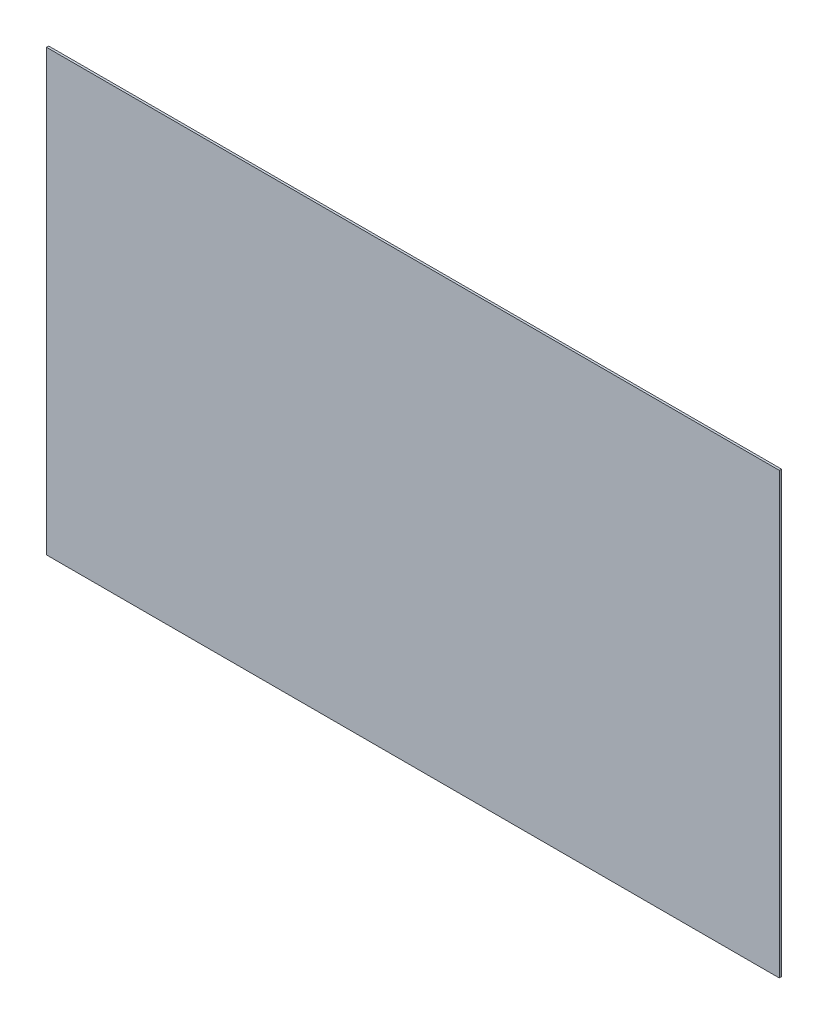
SolidWorks part; units mm, degrees
ref_plane "前视基准面" through (0, 0, 0) normal (0, 0, 1) x (1, 0, 0)
ref_plane "上视基准面" through (0, 0, 0) normal (0, 1, 0) x (1, 0, 0)
ref_plane "右视基准面" through (0, 0, 0) normal (1, 0, 0) x (0, 0, -1)
other "Configuration Table"
sketch "草图1" plane through (0, 0, 0) normal (0, 0, 1) x (1, 0, 0)
  line L1 (0, 0) -> (1000, 0)
  line L2 (0, 0) -> (0, 600)
  line L3 (0, 600) -> (1000, 600)
  line L4 (1000, 0) -> (1000, 600)
  dimension "D1" = 1000
  dimension "D2" = 600
extrude "凸台-拉伸1" add sketch "草图1" along normal blind 3
